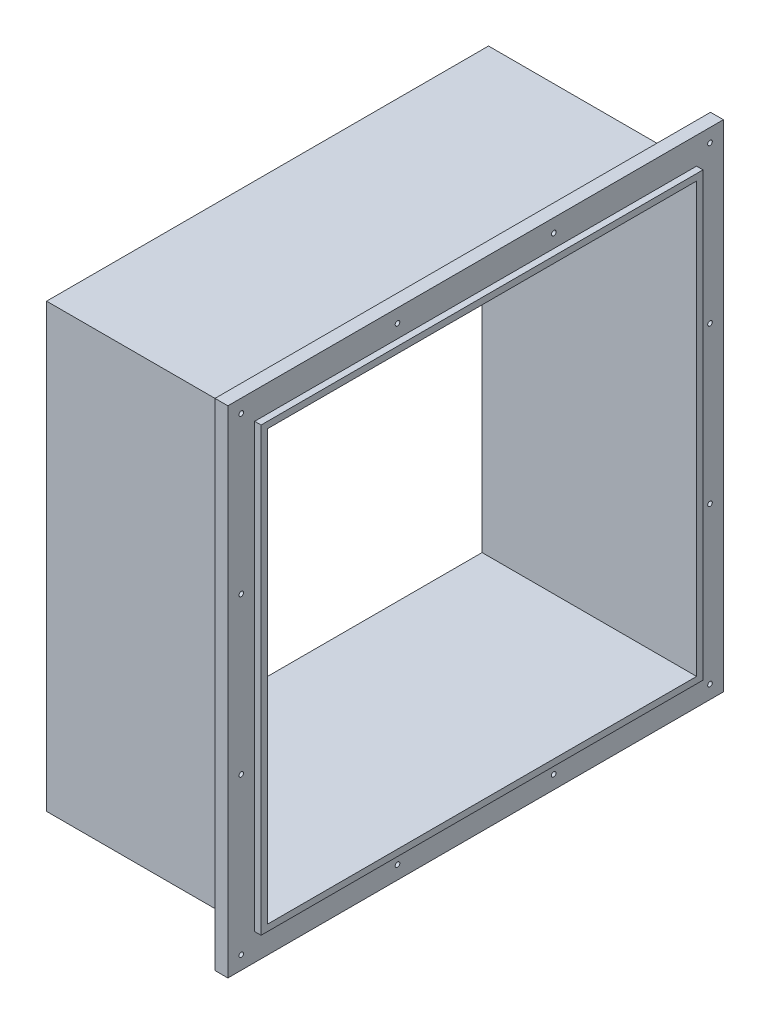
SolidWorks part; units mm, degrees
other "Markup1"
sketch "Sketch4" plane through (205, 243, -243) normal (0.9832, 0.1824, -0.0072) x (-0.0237, 0.0882, -0.9958)
material "Teak"
ref_plane "Front Plane" through (0, 0, 0) normal (0, 0, 1) x (1, 0, 0)
ref_plane "Top Plane" through (0, 0, 0) normal (0, 1, 0) x (1, 0, 0)
ref_plane "Right Plane" through (0, 0, 0) normal (1, 0, 0) x (0, 0, -1)
sketch "Sketch1" plane through (0, 0, 0) normal (1, 0, 0) x (0, 0, -1)
  line L1 (200, -200) -> (-200, -200)
  line L2 (200, -200) -> (200, 200)
  line L3 (200, 200) -> (-200, 200)
  line L4 (-200, -200) -> (-200, 200)
  line L5 (200, -200) -> (-200, 200) construction
  line L6 (200, 200) -> (-200, -200) construction
  point P0 (0, 0)
  dimension "D1" = 400
extrude "Extrude-Thin1" add sketch "Sketch1" along normal blind 200 thin thin type one direction wall 6
ref_plane "Plane1" through (194, 0, 0) normal (1, 0, 0) x (0, 0, -1)
sketch "Sketch5" plane through (194, 0, 0) normal (1, 0, 0) x (0, 0, -1)
  line L1 (206, -206) -> (-206, -206)
  line L2 (206, -206) -> (206, 206)
  line L3 (206, 206) -> (-206, 206)
  line L4 (-206, -206) -> (-206, 206)
  line L5 (206, -206) -> (-206, 206) construction
  line L6 (206, 206) -> (-206, -206) construction
  point P0 (0, 0)
extrude "Extrude-Thin2" add sketch "Sketch5" against normal blind 12 thin thin type one direction wall 25
sketch "Sketch6" plane through (194, 0, 0) normal (1, 0, 0) x (0, 0, -1)
  line L0 (206, 206) -> (231, 231) construction
  line L1 (-231, 231) -> (-206, 206) construction
  line L2 (-218.5, 218.5) -> (218.5, 218.5) construction
  line L4 (0, 0) -> (0, 349.226) construction
  line L5 (0, 0) -> (-338.552, 0) construction
  circle A0 centre (-218.5, 218.5) radius 2.15
  circle A1 centre (-72.83, 218.5) radius 2.15
  circle A2 centre (72.84, 218.5) radius 2.15
  circle A3 centre (-218.5, 72.83) radius 2.15
  circle A4 centre (-218.5, -72.84) radius 2.15
  circle A5 centre (218.5, 218.5) radius 2.15
  circle A6 centre (218.5, -218.5) radius 2.15
  circle A7 centre (72.84, -218.5) radius 2.15
  circle A8 centre (-72.83, -218.5) radius 2.15
  circle A9 centre (-218.5, -218.5) radius 2.15
  circle A10 centre (218.5, 72.83) radius 2.15
  circle A11 centre (218.5, -72.84) radius 2.15
  point P32 (0, 0)
  dimension "D1" = 4.3
  dimension "D5" = 145.67
  dimension "D2" = 145.67
  dimension "D3" = 145.67
  dimension "D4" = 3
extrude "Cut-Extrude1" cut sketch "Sketch6" against normal through all contours L1 A0 | L1 A0 | A1 | A2 | A4 | A8 | A7 | A11 | A3 | A9 | A6 | A10 | A5
